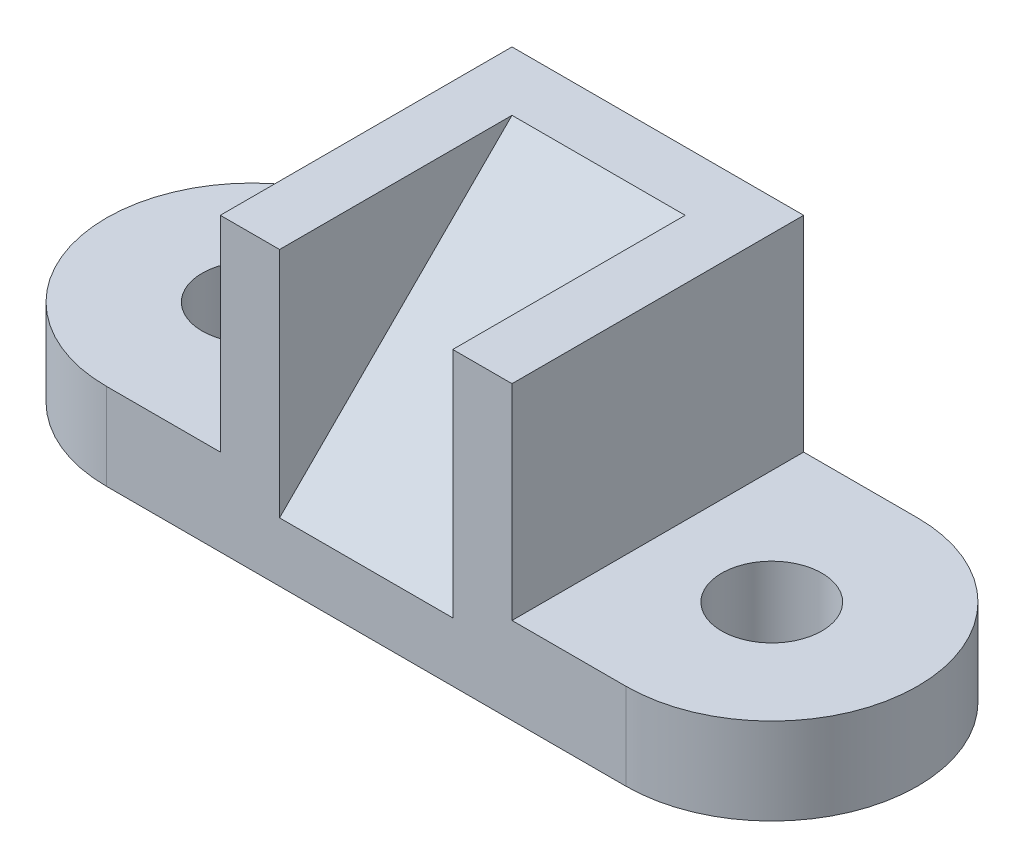
SolidWorks part; units mm, degrees
ref_plane "Front Plane" through (0, 0, 0) normal (0, 0, 1) x (1, 0, 0)
ref_plane "Top Plane" through (0, 0, 0) normal (0, 1, 0) x (1, 0, 0)
ref_plane "Right Plane" through (0, 0, 0) normal (1, 0, 0) x (0, 0, -1)
sketch "Sketch2" plane through (0, 0, 0) normal (0, 1, 0) x (1, 0, 0)
  line L1 (0, 32) -> (114, 32)
  line L2 (0, -32) -> (114, -32)
  circle A0 centre (0, 0) radius 11
  arc A1 (0, 32) -> (0, -32) centre (0, 0) ccw
  circle A2 centre (114, 0) radius 11
  arc A3 (114, -32) -> (114, 32) centre (114, 0) ccw
  point P6 (0, 0)
  dimension "D1" = 22
  dimension "D2" = 64
  dimension "D3" = 114
extrude "Boss-Extrude1" add sketch "Sketch2" along normal blind 19
sketch "Sketch3" plane through (0, 19, 0) normal (0, 1, 0) x (1, 0, 0)
  line L0 (114, 32) -> (0, 32) construction
  line L1 (25, 32) -> (89, 32)
  line L2 (25, 32) -> (25, -32)
  line L3 (25, -32) -> (89, -32)
  line L4 (89, 32) -> (89, -32)
  line L5 (0, -32) -> (114, -32) construction
  circle A0 centre (0, 0) radius 11 construction
  dimension "D1" = 64
  dimension "D2" = 25
extrude "Boss-Extrude2" add sketch "Sketch3" along normal blind 45
ref_plane "Plane1" through (57, 0, 0) normal (-1, 0, 0) x (0, 0, 1)
sketch "Sketch4" plane through (57, 0, 0) normal (-1, 0, 0) x (0, 0, 1)
  line L0 (-19, 64) -> (32, 13)
  line L1 (-32, 64) -> (32, 64) construction
  line L2 (32, 64) -> (32, 19) construction
  line L3 (32, 13) -> (32, 64)
  line L4 (32, 64) -> (-19, 64)
  line L5 (-32, 0) -> (32, 0) construction
  line L6 (-32, 64) -> (-32, 19) construction
  dimension "D1" = 13
  dimension "D2" = 13
extrude "Cut-Extrude1" cut sketch "Sketch4" against normal mid plane 38
